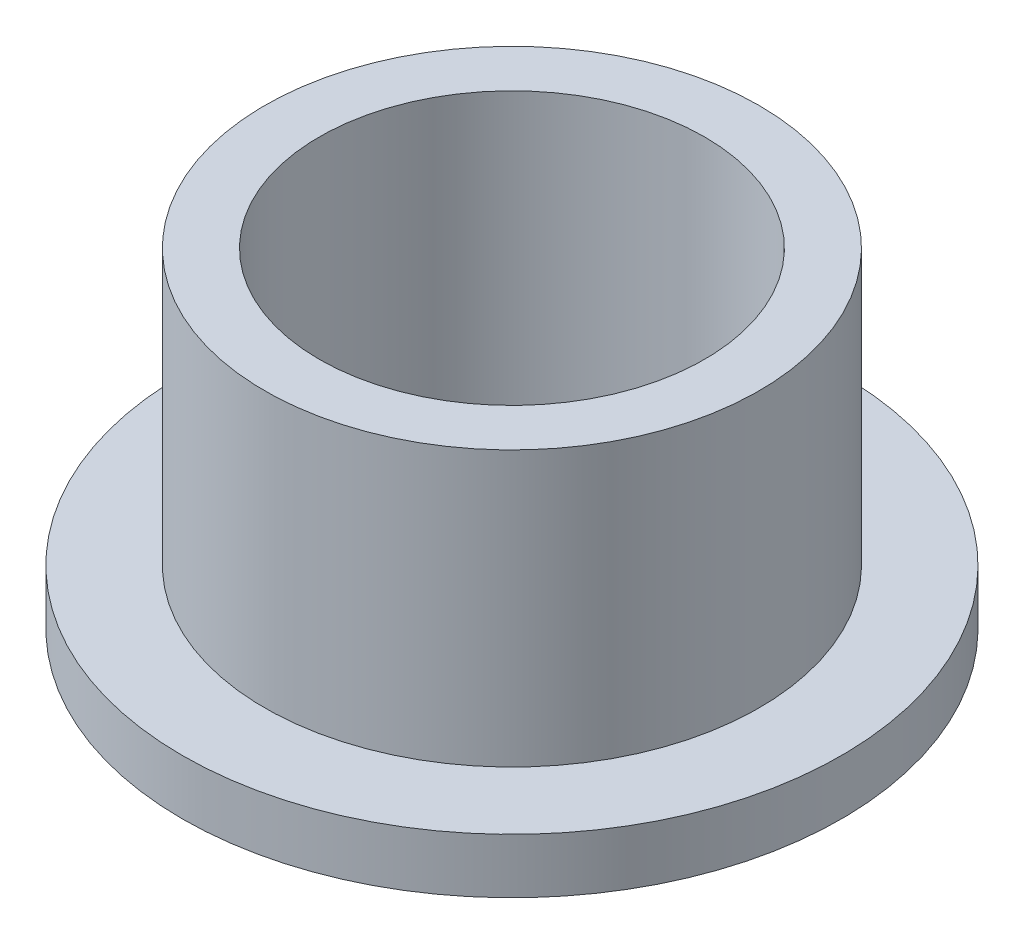
SolidWorks part; units mm, degrees
material "Phosphor bronze 10% D, UNS C52400"
ref_plane "Front" through (0, 0, 0) normal (0, 0, 1) x (1, 0, 0)
ref_plane "Top" through (0, 0, 0) normal (0, 1, 0) x (1, 0, 0)
ref_plane "Right" through (0, 0, 0) normal (1, 0, 0) x (0, 0, -1)
sketch "Sketch1" plane through (0, 0, 0) normal (0, 1, 0) x (1, 0, 0)
  circle A0 centre (0, 0) radius 11.1379
  circle A1 centre (0, 0) radius 14.2875
  circle A2 centre (0, 0) radius 19.05
  dimension "ID" = 22.2758
  dimension "OD" = 28.575
  dimension "FlangeOD" = 38.1
sketch "Sketch2" plane through (0, 0, 0) normal (0, 1, 0) x (1, 0, 0)
  circle A0 centre (0, 0) radius 11.1379 construction
  circle A1 centre (0, 0) radius 14.2875 construction
  circle A2 centre (0, 0) radius 11.1379
  circle A3 centre (0, 0) radius 14.2875
extrude "Boss-Extrude1" add sketch "Sketch2" along normal blind 19.05
sketch "Sketch3" plane through (0, 0, 0) normal (0, 1, 0) x (1, 0, 0)
  circle A0 centre (0, 0) radius 19.05 construction
  circle A1 centre (0, 0) radius 14.2875 construction
  circle A2 centre (0, 0) radius 19.05
  circle A3 centre (0, 0) radius 14.2875
extrude "Boss-Extrude2" add sketch "Sketch3" along normal blind 3.175
